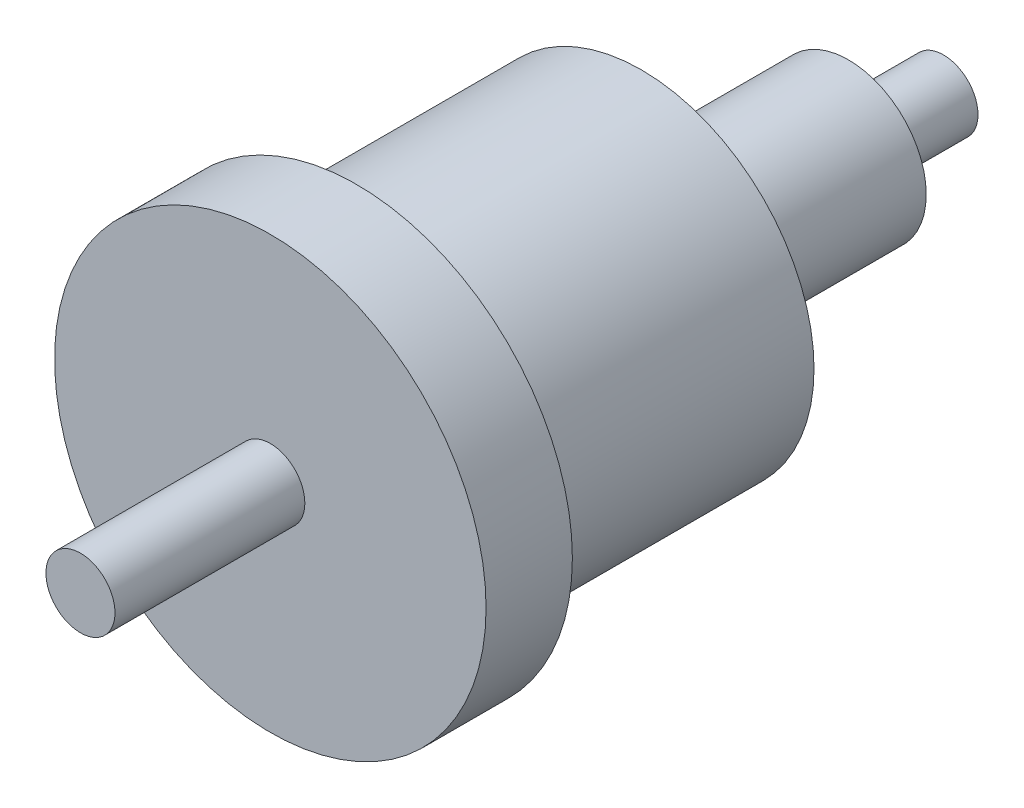
SolidWorks part; units mm, degrees
ref_plane "Front" through (0, 0, 0) normal (0, 0, 1) x (1, 0, 0)
ref_plane "Top" through (0, 0, 0) normal (0, 1, 0) x (1, 0, 0)
ref_plane "Right" through (0, 0, 0) normal (1, 0, 0) x (0, 0, -1)
sketch "Sketch1" plane through (0, 0, 0) normal (0, 0, 1) x (1, 0, 0)
  circle A0 centre (0, 0) radius 0.4
  dimension "D1" = 0.8
extrude "Boss-Extrude1" add sketch "Sketch1" along normal blind 1.1
sketch "Sketch2" plane through (0, 0, 1.1) normal (0, 0, 1) x (1, 0, 0)
  circle A0 centre (0, 0) radius 0.9
  dimension "D1" = 1.8
extrude "Boss-Extrude2" add sketch "Sketch2" along normal blind 2.4
sketch "Sketch3" plane through (0, 0, 3.5) normal (0, 0, 1) x (1, 0, 0)
  circle A0 centre (0, 0) radius 2
  dimension "D1" = 4
extrude "Boss-Extrude3" add sketch "Sketch3" along normal blind 3.3
sketch "Sketch4" plane through (0, 0, 6.8) normal (0, 0, 1) x (1, 0, 0)
  circle A0 centre (0, 0) radius 2.5
  dimension "D1" = 5
extrude "Boss-Extrude4" add sketch "Sketch4" along normal blind 1
sketch "Sketch5" plane through (0, 0, 7.8) normal (0, 0, 1) x (1, 0, 0)
  circle A0 centre (0, 0) radius 0.4
  dimension "D1" = 0.8
extrude "Boss-Extrude5" add sketch "Sketch5" along normal blind 2.2
